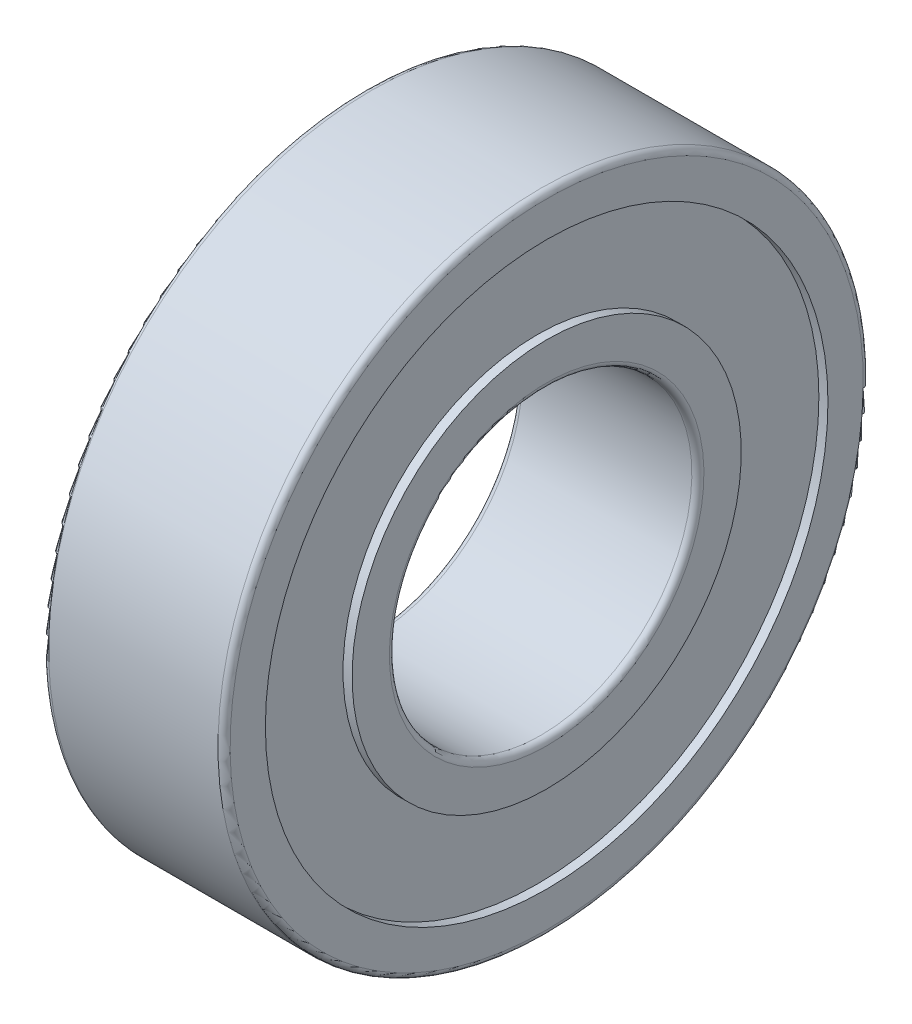
SolidWorks part; units mm, degrees
ref_plane "Front Plane" through (0, 0, 0) normal (0, 0, 1) x (1, 0, 0)
ref_plane "Top Plane" through (0, 0, 0) normal (0, 1, 0) x (1, 0, 0)
ref_plane "Right Plane" through (0, 0, 0) normal (1, 0, 0) x (0, 0, -1)
sketch "Sketch1" plane through (0, 0, 0) normal (0, 0, 1) x (1, 0, 0)
  line L0 (0, 0) -> (9, 0) construction
  line L1 (0, 7.5) -> (0, 9.65)
  line L2 (0, 9.65) -> (0.45, 9.65)
  line L3 (0.45, 9.65) -> (0.45, 13.95)
  line L4 (0.45, 13.95) -> (0, 13.95)
  line L5 (0, 13.95) -> (0, 16)
  line L6 (0, 16) -> (9, 16)
  line L7 (9, 16) -> (9, 13.95)
  line L8 (9, 13.95) -> (8.55, 13.95)
  line L9 (8.55, 13.95) -> (8.55, 9.65)
  line L10 (8.55, 9.65) -> (9, 9.65)
  line L11 (9, 9.65) -> (9, 7.5)
  line L12 (9, 7.5) -> (0, 7.5)
  dimension "D_s" = 15
  dimension "D" = 32
  dimension "B" = 9
  dimension "MSM_3" = 19.3
  dimension "MSM_4" = 27.9
  dimension "MSM_5" = 8.1
revolve "Revolve1" add sketch "Sketch1" angle 360 about L0
fillet "Fillet1" radius 0.3 4 edges at (0, -7.5, 0) (9, -7.5, 0) (0, -16, 0) (9, -16, 0)
